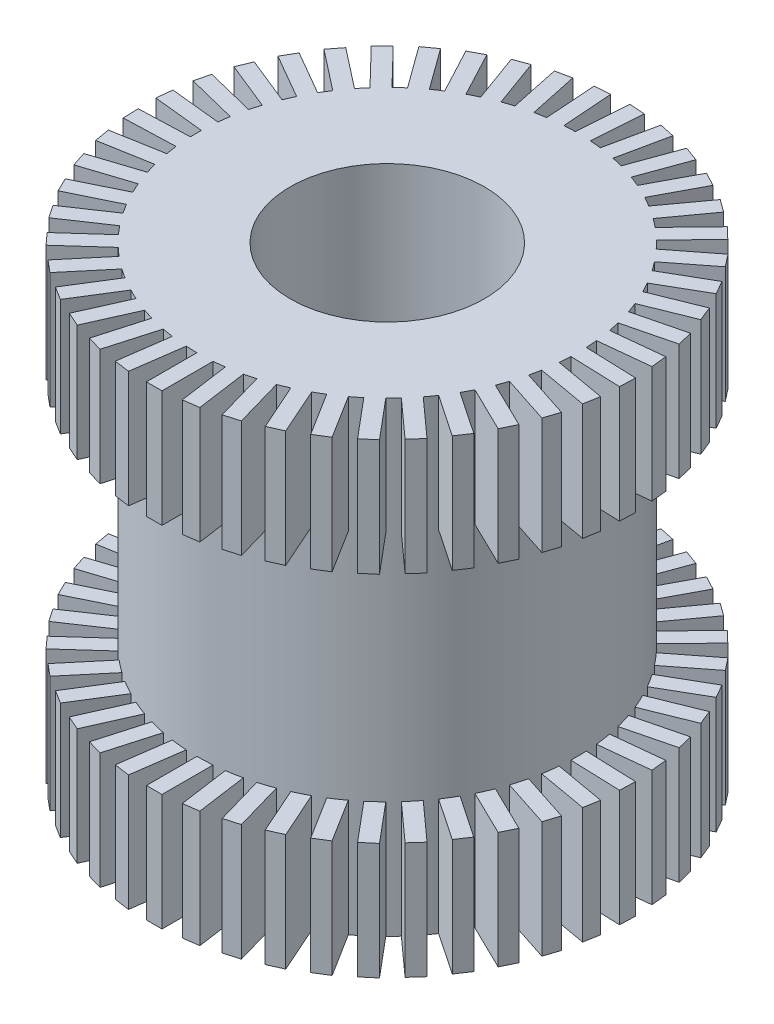
SolidWorks part; units mm, degrees
material "Brass"
ref_plane "Front Plane" through (0, 0, 0) normal (0, 0, 1) x (1, 0, 0)
ref_plane "Top Plane" through (0, 0, 0) normal (0, 1, 0) x (1, 0, 0)
ref_plane "Right Plane" through (0, 0, 0) normal (1, 0, 0) x (0, 0, -1)
sketch "Sketch1" plane through (0, 0, 0) normal (0, 1, 0) x (1, 0, 0)
  circle A0 centre (0, 0) radius 2.45
  dimension "D1" = 4.9
extrude "Boss-Extrude1" add sketch "Sketch1" along normal blind 6
hole_wizard "M3x0.5 Tapped Hole1" positions "Sketch2" profile "Sketch3" tap size "M3x0.5" standard "ANSI Metric" end condition through all
sketch "Sketch2" plane through (0, 6, 0) normal (0, 1, 0) x (1, 0, 0)
  point P0 (0, 0)
sketch "Sketch3" plane through (0, 6, 0) normal (1, 0, 0) x (0, 0, 1)
  line L0 (0, 0) -> (0, 6)
  line L1 (0, 6) -> (1.25, 6)
  line L2 (1.25, 6) -> (1.25, 0)
  line L5 (1.25, 0) -> (0, 0)
  line L11 (0, -6.35) -> (0, 107.95) construction
  dimension "Thru Tap Drill Dia." = 2.5
  dimension "Thru Tap Drill Depth" = 6
cosmetic thread "Hole Thread1" parameters "D2"=3
ref_plane "Plane1" through (0, 0, 3) normal (0, 0, 1) x (1, 0, 0)
sketch "Sketch4" plane through (0, 0, 3) normal (0, 0, 1) x (1, 0, 0)
  line L0 (2.45, 6) -> (-2.45, 6) construction
  line L1 (0.2, 6) -> (0, 6)
  line L2 (0.2, 6) -> (0.2, 4.5)
  line L3 (0.2, 4.5) -> (0, 4.5)
  line L4 (0, 6) -> (0, 4.5)
  line L5 (0, -55) -> (0, 55) construction
  line L7 (0, 0) -> (0.2, 0)
  line L8 (0, 0) -> (0, 1.5)
  line L9 (0, 1.5) -> (0.2, 1.5)
  line L10 (0.2, 0) -> (0.2, 1.5)
  dimension "D1" = 0.2
  dimension "D2" = 1.5
  dimension "D3" = 1.5
  dimension "D4" = 0.2
extrude "Boss-Extrude2" add sketch "Sketch4" along normal blind 0.1 and the other way up to surface other way up to face at (0, 6, 2.45)
pattern_circular "CirPattern1" count 45 over 360 about axis through (0, 0, 0) along (0, 1, 0) of "Boss-Extrude2"
